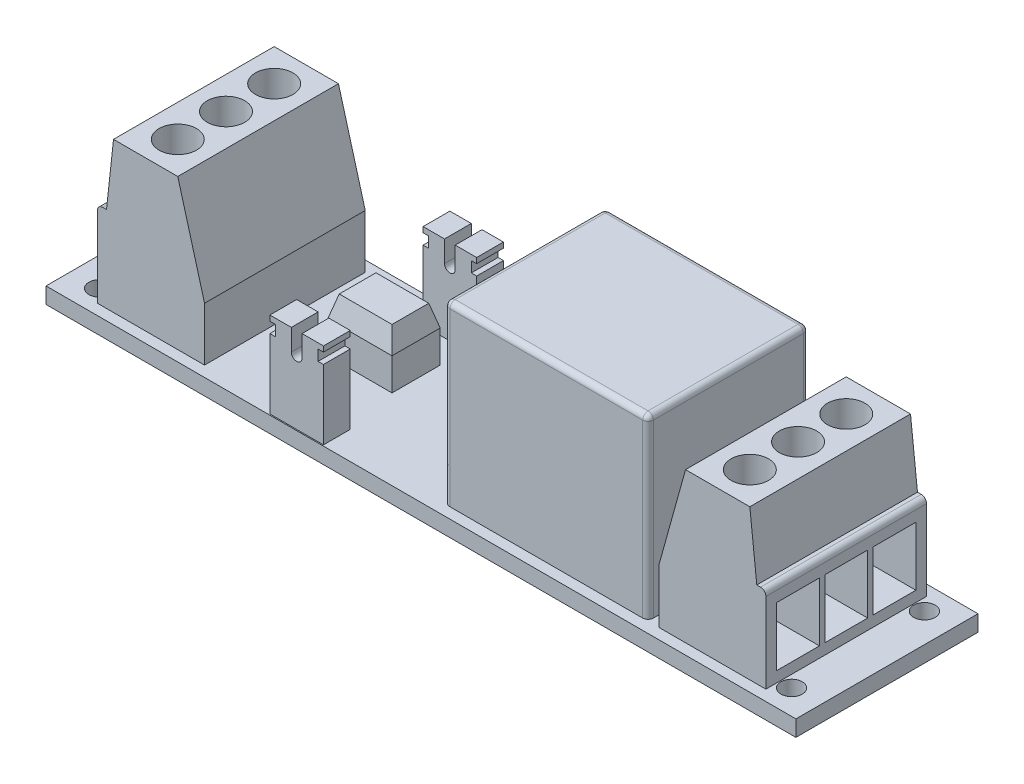
SolidWorks part; units mm, degrees
material "3.3V_RELAY_AVG"
ref_plane "Front Plane" through (0, 0, 0) normal (0, 0, 1) x (1, 0, 0)
ref_plane "Top Plane" through (0, 0, 0) normal (0, 1, 0) x (1, 0, 0)
ref_plane "Right Plane" through (0, 0, 0) normal (1, 0, 0) x (0, 0, -1)
sketch "Sketch1" plane through (0, 0, 0) normal (0, 1, 0) x (1, 0, 0)
  line L0 (-31.3, 6.0031) -> (-31.3, 50006.0031) construction
  line L1 (35, 8.5) -> (-35, 8.5)
  line L2 (35, 8.5) -> (35, -8.5)
  line L3 (35, -8.5) -> (-35, -8.5)
  line L4 (-35, 8.5) -> (-35, -8.5)
  line L5 (35, 8.5) -> (-35, -8.5) construction
  line L6 (35, -8.5) -> (-35, 8.5) construction
  line L7 (-31.8543, 5.2) -> (-50031.8543, 5.2) construction
  line L8 (31.3, 5.6691) -> (31.3, 50005.6691) construction
  line L9 (-34.1148, -5.2) -> (49965.8852, -5.2) construction
  line L10 (0, 0) -> (50000, 0) construction
  line L11 (0, 0) -> (0, 50000) construction
  circle A0 centre (-32.3, 6.2) radius 1
  circle A1 centre (32.3, 6.2) radius 1
  circle A2 centre (32.3, -6.2) radius 1
  circle A3 centre (-32.3, -6.2) radius 1
  point P0 (0, 0)
  dimension "D1" = 2
  dimension "D2" = 2
  dimension "D3" = 2
  dimension "D4" = 2
  dimension "D5" = 62.6
  dimension "D6" = 10.4
  dimension "D7" = 70
  dimension "D8" = 17
extrude "Boss-Extrude1" add sketch "Sketch1" along normal blind 1.5
sketch "Sketch2" plane through (0, 0, 0) normal (0, 0, 1) x (1, 0, 0)
  line L0 (-35, 1.5) -> (35, 1.5) construction
  line L1 (-21.2, 15.5) -> (-31.2, 15.5) construction
  line L2 (-21.2, 15.5) -> (-21.2, 1.5) construction
  line L3 (-21.2, 1.5) -> (-31.2, 1.5) construction
  line L4 (-31.2, 15.5) -> (-31.2, 1.5) construction
  line L5 (-21.2, 15.5) -> (-31.2, 1.5) construction
  line L6 (-21.2, 1.5) -> (-31.2, 15.5) construction
  line L7 (-31.3, 1.5) -> (-33.3, 1.5) construction
  line L8 (-31.3, 1.5) -> (-33.3, 1.5) construction
  line L9 (-31.2, 1.5) -> (-31.2, 9.5)
  line L10 (-31.2, 9.5) -> (-30.3507, 9.5)
  line L11 (-30.3507, 9.5) -> (-29.7, 15.5)
  line L12 (-29.7, 15.5) -> (-23.7, 15.5)
  line L13 (-23.7, 15.5) -> (-21.2, 6.5)
  line L14 (-21.2, 6.5) -> (-21.2, 1.5)
  line L15 (-21.2, 1.5) -> (-31.2, 1.5)
  point P0 (-26.2, 8.5)
  dimension "D1" = 10
  dimension "D2" = 14
  dimension "D3" = 0.1
  dimension "D4" = 8
  dimension "D5" = 6
  dimension "D6" = 5
  dimension "D7" = 1.5
extrude "Boss-Extrude2" add sketch "Sketch2" along normal offset from surface 1 and the other way offset from surface (7.5 mm away) 1 up to face at (0, 0.75, 8.5) other way up to face at (0, 0.75, -8.5)
fillet "Fillet1" radius 0.5 1 edges at (-31.2, 9.5, 0)
sketch "Sketch3" plane through (0, 15.5, 0) normal (0, 1, 0) x (1, 0, 0)
  line L0 (-26.7, 1.8384) -> (-26.7, -4.138) construction
  line L1 (-23.7, -7.5) -> (-23.7, 7.5) construction
  line L2 (-29.7, -7.5) -> (-29.7, 7.5) construction
  line L3 (0, 0) -> (-50000, 0) construction
  circle A0 centre (-26.7, 4.5) radius 1.75
  circle A1 centre (-26.7, 0) radius 1.75
  circle A2 centre (-26.7, -4.5) radius 1.75
  dimension "D1" = 3.5
  dimension "D2" = 4.5
  dimension "D3" = 4.5
extrude "Cut-Extrude1" cut sketch "Sketch3" against normal blind 11
sketch "Sketch4" plane through (-31.2, 0, 0) normal (-1, 0, 0) x (0, 0, 1)
  line L0 (6.25, 15.5) -> (2.75, 15.5) construction
  line L1 (1.75, 15.5) -> (-1.75, 15.5) construction
  line L2 (-2.75, 15.5) -> (-6.25, 15.5) construction
  line L3 (6.25, 15.5) -> (2.75, 15.5) construction
  line L4 (7.5, 1.5) -> (7.5, 9)
  line L5 (7.5, 9) -> (-7.5, 9)
  line L6 (-7.5, 9) -> (-7.5, 1.5)
  line L7 (-7.5, 1.5) -> (7.5, 1.5)
  line L8 (7.5, 1.5) -> (7.5, 9) construction
  line L9 (7.5, 9) -> (-7.5, 9) construction
  line L10 (-7.5, 9) -> (-7.5, 1.5) construction
  line L11 (-7.5, 1.5) -> (7.5, 1.5) construction
  line L12 (1.75, 15.5) -> (-1.75, 15.5) construction
  line L13 (-2.75, 15.5) -> (-6.25, 15.5) construction
  line L14 (-4.5, 15.5) -> (-4.5, 50015.5) construction
  line L15 (0, 15.5) -> (0, 50015.5) construction
  line L16 (4.5, 15.5) -> (4.5, 50015.5) construction
  line L18 (-6.5, 2.5) -> (-2.5, 2.5)
  line L19 (-6.5, 2.5) -> (-6.5, 8)
  line L20 (-6.5, 8) -> (-2.5, 8)
  line L21 (-2.5, 2.5) -> (-2.5, 8)
  line L22 (-6.5, 2.5) -> (-2.5, 8) construction
  line L23 (-6.5, 8) -> (-2.5, 2.5) construction
  line L24 (-2, 2.5) -> (2, 2.5)
  line L25 (-2, 2.5) -> (-2, 8)
  line L26 (-2, 8) -> (2, 8)
  line L27 (2, 2.5) -> (2, 8)
  line L28 (-2, 2.5) -> (2, 8) construction
  line L29 (-2, 8) -> (2, 2.5) construction
  line L30 (2.5, 2.5) -> (6.5, 2.5)
  line L31 (2.5, 2.5) -> (2.5, 8)
  line L32 (2.5, 8) -> (6.5, 8)
  line L33 (6.5, 2.5) -> (6.5, 8)
  line L34 (2.5, 2.5) -> (6.5, 8) construction
  line L35 (2.5, 8) -> (6.5, 2.5) construction
  point P12 (-4.5, 15.5)
  point P15 (0, 15.5)
  point P18 (4.5, 15.5)
  point P19 (-4.5, 5.25)
  point P24 (0, 5.25)
  point P29 (4.5, 5.25)
  dimension "D2" = 4
  dimension "D3" = 1
  dimension "D4" = 1
  dimension "D1" = 0
extrude "Cut-Extrude2" cut sketch "Sketch4" against normal blind 7
mirror "Mirror1" about plane through (0, 0, 0) normal (1, 0, 0) of "Cut-Extrude2", "Cut-Extrude1", "Fillet1", "Boss-Extrude2"
sketch "Sketch5" plane through (0, 1.5, 0) normal (0, 1, 0) x (1, 0, 0)
  line L0 (0, 0) -> (50000, 0) construction
  line L1 (21.2, 7.5) -> (31.2, 7.5) construction
  line L2 (1.2, 7.5) -> (20.2, 7.5)
  line L3 (1.2, 7.5) -> (1.2, -7.5)
  line L4 (1.2, -7.5) -> (20.2, -7.5)
  line L5 (20.2, 7.5) -> (20.2, -7.5)
  line L6 (1.2, 7.5) -> (20.2, -7.5) construction
  line L7 (1.2, -7.5) -> (20.2, 7.5) construction
  line L8 (29.7, -7.5) -> (23.7, -7.5) construction
  line L10 (21.2, -7.5) -> (21.2, 7.5) construction
  point P3 (9.9228, 0.2105)
  dimension "D1" = 19
  dimension "D2" = 1
extrude "Boss-Extrude3" add sketch "Sketch5" along normal blind 16.5
fillet "Fillet2" radius 0.5 8 edges at (20.2, 9.75, 7.5) (20.2, 9.75, -7.5) (1.2, 9.75, 7.5) (1.2, 9.75, -7.5) (10.7, 18, -7.5) (1.2, 18, 0) (10.7, 18, 7.5) (20.2, 18, 0)
sketch "Sketch6" plane through (0, 1.5, 0) normal (0, 1, 0) x (1, 0, 0)
  line L0 (-21.2, -7.5) -> (-21.2, 7.5) construction
  line L1 (35, 8.5) -> (-35, 8.5) construction
  line L2 (-10.2, 3.5) -> (-16.2, 3.5)
  line L3 (-10.2, 3.5) -> (-10.2, -1)
  line L4 (-10.2, -1) -> (-16.2, -1)
  line L5 (-16.2, 3.5) -> (-16.2, -1)
  line L6 (-10.2, 3.5) -> (-16.2, -1) construction
  line L7 (-10.2, -1) -> (-16.2, 3.5) construction
  point P2 (-13.2, 1.25)
  dimension "D1" = 6
  dimension "D2" = 4.5
  dimension "D3" = 5
  dimension "D4" = 5
extrude "Boss-Extrude4" add sketch "Sketch6" along normal blind 5
chamfer "Chamfer1" distance 2 angle 15 4 edges at (-10.2, 6.5, -1.25) (-13.2, 6.5, 1) (-16.2, 6.5, -1.25) (-13.2, 6.5, -3.5)
sketch "Sketch7" plane through (0, 1.5, 0) normal (0, 1, 0) x (1, 0, 0)
  line L1 (-14.2, -8.4) -> (-9.2, -8.4)
  line L2 (-14.2, -8.4) -> (-14.2, -5.9)
  line L3 (-14.2, -5.9) -> (-9.2, -5.9)
  line L4 (-9.2, -8.4) -> (-9.2, -5.9)
  line L5 (-14.2, -8.4) -> (-9.2, -5.9) construction
  line L6 (-14.2, -5.9) -> (-9.2, -8.4) construction
  line L7 (-21.2, -7.5) -> (-21.2, 7.5) construction
  line L8 (-35, -8.5) -> (35, -8.5) construction
  point P4 (-11.7, -7.15)
  dimension "D1" = 5
  dimension "D2" = 7
  dimension "D3" = 2.5
  dimension "D4" = 0.1
extrude "Boss-Extrude5" add sketch "Sketch7" along normal blind 8
sketch "Sketch8" plane through (0, 0, 8.4) normal (0, 0, 1) x (1, 0, 0)
  line L0 (-11.7, 9.5) -> (-11.7, 50009.5) construction
  line L1 (-14.2, 9) -> (-13.7, 9)
  line L2 (-14.2, 9) -> (-14.2, 8)
  line L3 (-14.2, 8) -> (-13.7, 8)
  line L4 (-14.2, 1.5) -> (-9.2, 1.5)
  line L5 (-9.2, 1.5) -> (-9.2, 9.5)
  line L6 (-9.2, 9.5) -> (-14.2, 9.5)
  line L7 (-14.2, 9.5) -> (-14.2, 1.5)
  line L8 (-14.2, 1.5) -> (-9.2, 1.5) construction
  line L9 (-9.2, 1.5) -> (-9.2, 9.5) construction
  line L10 (-9.2, 9.5) -> (-14.2, 9.5) construction
  line L11 (-14.2, 9.5) -> (-14.2, 1.5) construction
  line L12 (-13.7, 9) -> (-13.7, 8)
  line L13 (-14.2, 9) -> (-13.7, 8) construction
  line L14 (-14.2, 8) -> (-13.7, 9) construction
  line L15 (-12.2, 7.5) -> (-12.2, 9.5)
  line L16 (-11.2, 7.5) -> (-11.2, 9.5)
  line L17 (-9.2, 8) -> (-9.7, 9) construction
  line L18 (-9.2, 9) -> (-9.7, 8) construction
  line L19 (-9.2, 9) -> (-9.2, 8)
  line L20 (-9.2, 8) -> (-9.7, 8)
  line L21 (-9.7, 9) -> (-9.7, 8)
  line L22 (-9.2, 9) -> (-9.7, 9)
  line L23 (-12.2, 9.5) -> (-11.2, 9.5)
  arc A0 (-12.2, 7.5) -> (-11.2, 7.5) centre (-11.7, 7.5) ccw
  point P8 (-13.95, 8.5)
  point P13 (-11.7, 9.5)
  dimension "D5" = 1
  dimension "D2" = 1
  dimension "D3" = 0.5
  dimension "D4" = 0.5
  dimension "D6" = 2
  dimension "D1" = 0
extrude "Cut-Extrude3" cut sketch "Sketch8" against normal up to next
mirror "Mirror2" about plane through (0, 0, 0) normal (0, 0, 1) of "Cut-Extrude3", "Boss-Extrude5"
